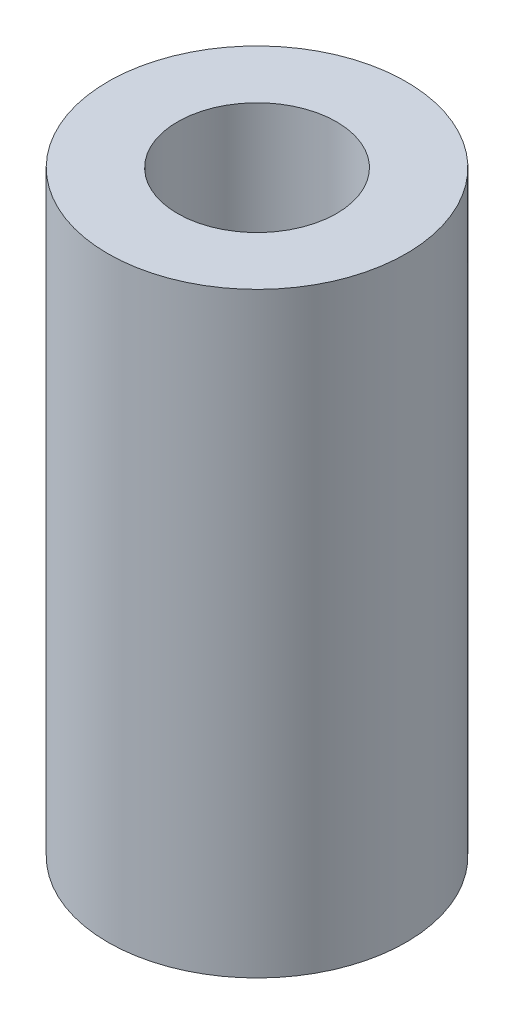
SolidWorks part; units mm, degrees
ref_plane "Alzado" through (0, 0, 0) normal (0, 0, 1) x (1, 0, 0)
ref_plane "Planta" through (0, 0, 0) normal (0, 1, 0) x (1, 0, 0)
ref_plane "Vista lateral" through (0, 0, 0) normal (1, 0, 0) x (0, 0, -1)
sketch "Croquis1" plane through (0, 0, 0) normal (0, 1, 0) x (1, 0, 0)
  circle A0 centre (0, 0) radius 4
  circle A1 centre (0, 0) radius 7.5
  dimension "D1" = 8
  dimension "D2" = 15
extrude "Saliente-Extruir1" add sketch "Croquis1" along normal blind 30
sketch "Croquis2" plane through (0, 0, 0) normal (0, -1, 0) x (1, 0, 0)
  line L0 (0, 0) -> (0, 2.9) construction
  line L1 (0, 2.9) -> (0, 8.2816) construction
  line L2 (3.45, 2.9) -> (-3.45, 2.9)
  line L3 (0, 0) -> (0, -4) construction
  line L4 (-3.45, 2.9) -> (-3.45, 6.3264)
  line L5 (-3.45, 6.3264) -> (3.45, 6.3264)
  line L6 (3.45, 6.3264) -> (3.45, 2.9)
  circle A0 centre (0, 0) radius 4 construction
  point P8 (0, 2.9)
  dimension "D2" = 6.9
  dimension "D1" = 6.9
extrude "Saliente-Extruir2" add sketch "Croquis2" against normal blind 20
sketch "Croquis3" plane through (0, 30, 0) normal (0, 1, 0) x (1, 0, 0)
  circle A0 centre (0, 0) radius 3.925
  dimension "D1" = 7.85
extrude "Cortar-Extruir1" cut sketch "Croquis3" against normal blind 20
